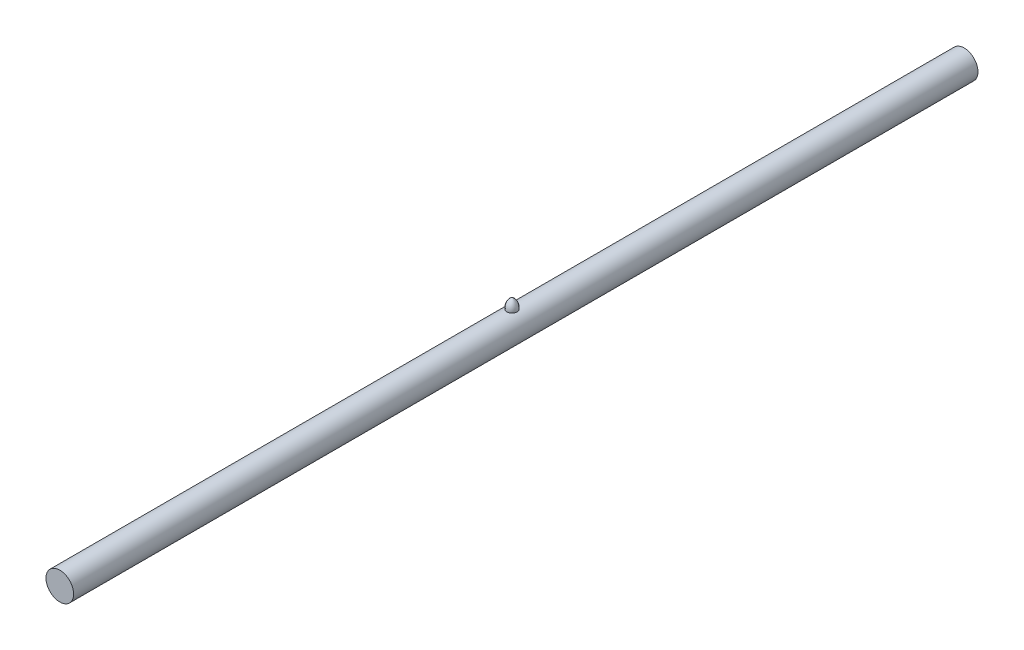
SolidWorks part; units mm, degrees
ref_plane "Front Plane" through (0, 0, 0) normal (0, 0, 1) x (1, 0, 0)
ref_plane "Top Plane" through (0, 0, 0) normal (0, 1, 0) x (1, 0, 0)
ref_plane "Right Plane" through (0, 0, 0) normal (1, 0, 0) x (0, 0, -1)
sketch "Sketch1" plane through (0, 0, 0) normal (0, 0, 1) x (1, 0, 0)
  circle A0 centre (0, 0) radius 3.4925
  dimension "D1" = 6.985
extrude "Boss-Extrude1" add sketch "Sketch1" along normal blind 228.6
ref_plane "Plane1" through (0, 0, 114.3) normal (0, 0, 1) x (1, 0, 0)
sketch "Sketch2" plane through (0, 0, 0) normal (1, 0, 0) x (0, 0, -1)
  line L0 (-114.3, 3.4925) -> (-114.3, 6.0325) construction
  line L1 (0, 3.4925) -> (-228.6, 3.4925) construction
  line L2 (0, 3.4925) -> (-114.3, 3.4925) construction
  line L3 (0, -3.4925) -> (0, 3.4925) construction
  line L6 (-113.03, 3.4925) -> (-114.3, 3.4925)
  line L7 (-114.3, 6.0325) -> (-114.3, 3.4925)
  arc A0 (-113.03, 3.4925) -> (-114.3, 6.0325) centre (-115.5487, 3.8206) ccw
  dimension "D1" = 114.3
  dimension "D2" = 1.27
  dimension "D5" = 2.54
  dimension "D3" = 2.54
revolve "Revolve1" add sketch "Sketch2" angle 360 about L7
